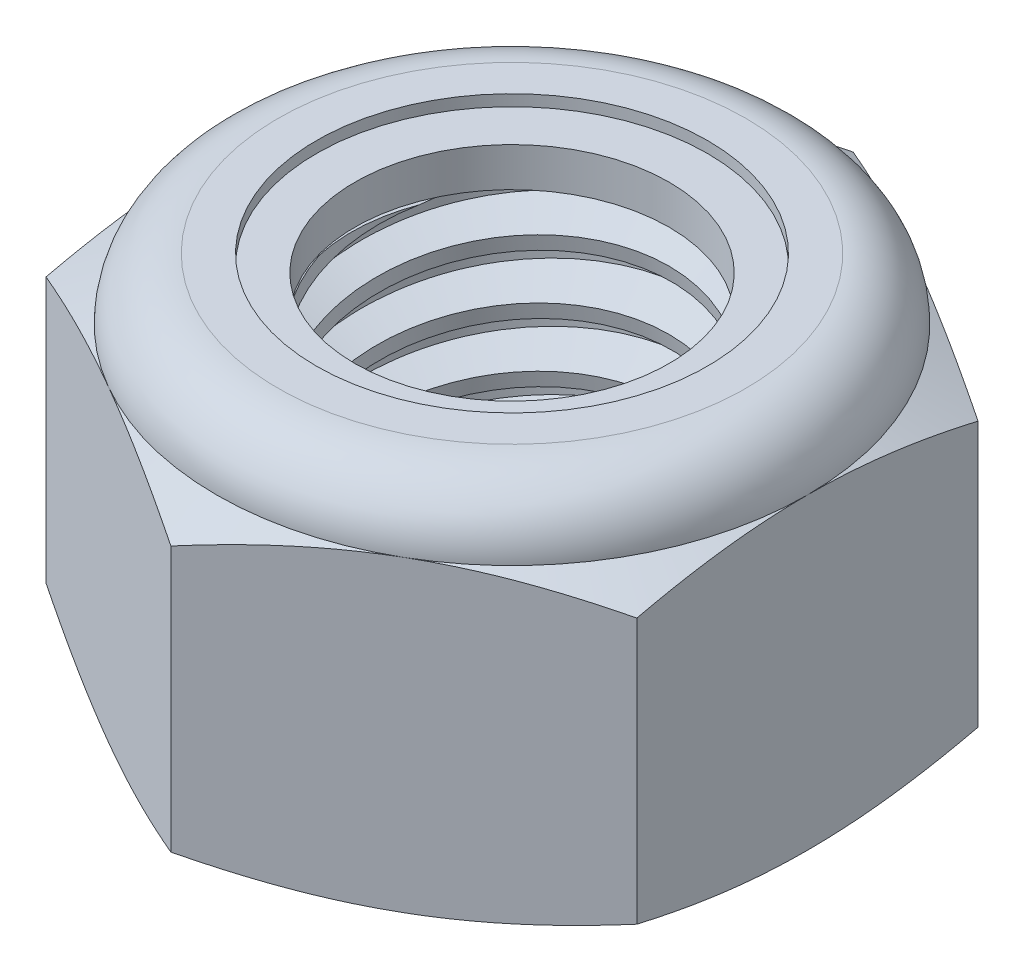
SolidWorks part; units mm, degrees
material "Stainless Steel (ferritic)"
ref_plane "Front" through (0, 0, 0) normal (0, 0, 1) x (1, 0, 0)
ref_plane "Top" through (0, 0, 0) normal (0, 1, 0) x (1, 0, 0)
ref_plane "Right" through (0, 0, 0) normal (1, 0, 0) x (0, 0, -1)
sketch "Sketch1" plane through (0, 0, 0) normal (0, 1, 0) x (1, 0, 0)
  line L1 (0, 4.6188) -> (-4, 2.3094)
  line L2 (-4, 2.3094) -> (-4, -2.3094)
  line L3 (-4, -2.3094) -> (0, -4.6188)
  line L4 (0, -4.6188) -> (4, -2.3094)
  line L5 (4, -2.3094) -> (4, 2.3094)
  line L6 (4, 2.3094) -> (0, 4.6188)
  circle A0 centre (0, 0) radius 4 construction
  dimension "Hex Flats" = 8
extrude "Extrude1" add sketch "Sketch1" along normal blind 5
sketch "Sketch2" plane through (0, 0, 0) normal (1, 0, 0) x (0, 0, -1)
  line L0 (-2.5, 0) -> (-2.5, 5) construction
  line L1 (0, 0) -> (2.5, 0)
  line L2 (0, 0) -> (0, 5)
  line L3 (0, 5) -> (2.5, 5)
  line L4 (2.5, 0) -> (2.5, 5)
  line L5 (-2.3094, 5) -> (2.3094, 5) construction
  line L7 (0, -2.5) -> (0, 0) construction
  dimension "Thread Dia" = 5
revolve "Revolve1" add sketch "Sketch2" angle 360 about L7
sketch "Sketch3" plane through (0, 0, 0) normal (1, 0, 0) x (0, 0, -1)
  line L0 (2.5, 5) -> (-2.5, 5) construction
  line L1 (-2.5, 5) -> (-2.5, 4.2) construction
  line L2 (-2.5, 4.2) -> (2.5, 5) construction
  line L3 (2.5, 5) -> (2.5158, 4.9013) construction
  line L4 (2.5158, 4.9013) -> (2.6264, 4.21)
  line L5 (2.6264, 4.21) -> (2.1593, 4.3885)
  line L6 (2.1593, 4.3885) -> (2.1277, 4.586)
  line L7 (2.1277, 4.586) -> (2.5158, 4.9013)
  line L8 (2.1435, 4.4872) -> (2.5711, 4.5557) construction
  line L9 (2.5, 5) -> (2.5, 4.5443) construction
  line L10 (2.5, 4.5443) -> (-2.5, 3.7443) construction
  line L11 (-2.5, 3.7443) -> (-2.5, 4.2) construction
  line L12 (-0.1369, 5) -> (0.1369, 3.2886) construction
  line L13 (-2.5, 0) -> (-2.5, 5) construction
  line L14 (0, 5) -> (2.5, 5) construction
  line L15 (2.5, 0) -> (2.5, 5) construction
  point P13 (0, 4.1443)
  dimension "D1" = 0.1
  dimension "D2" = 0.2
  dimension "Thread Pitch" = 0.8
  dimension "D4" = 60
  dimension "D5" = 0.8
revolve "Cut-Revolve1" cut sketch "Sketch3" angle 360 about L12
pattern_linear "LPattern1" count 6 spacing 0.8 along (0, -1, 0) count 2 spacing 0.8 along (0, 1, 0) of "Cut-Revolve1"
sketch "Sketch4" plane through (0, 0, 0) normal (1, 0, 0) x (0, 0, -1)
  line L0 (0, 5) -> (2.5, 5)
  line L1 (2.5, 5) -> (2.1277, 4.8264)
  line L2 (2.1277, 4.8264) -> (2.1277, 0.1736)
  line L3 (2.1277, 0.1736) -> (2.5, 0)
  line L4 (2.5, 0) -> (0, 0)
  line L5 (0, 0) -> (0, 5)
  line L6 (2.5, 0) -> (2.5, 5) construction
  line L7 (0, 5) -> (2.5, 5) construction
  line L8 (0, 0) -> (2.5, 0) construction
  line L9 (0, 0) -> (0, 5) construction
  line L10 (0, 5) -> (0, 5.4108) construction
  dimension "D1" = 25
revolve "Cut-Revolve2" cut sketch "Sketch4" angle 360 about L10
combine bodies "Combine1" operation type subtract main body 112 bodies to subtract 111
sketch "Sketch5" plane through (0, 0, 0) normal (1, 0, 0) x (0, 0, -1)
  line L0 (0, 0) -> (4, 0)
  line L1 (4, 0) -> (4.6188, 0.2886)
  line L2 (4.6188, 0.2886) -> (4.6188, 3.8781)
  line L3 (4.6188, 3.8781) -> (4, 4.1667)
  line L4 (3.1667, 5) -> (3.1667, 6.27)
  line L5 (3.1667, 6.27) -> (5.8888, 6.27)
  line L6 (5.8888, 6.27) -> (5.8888, -1.27)
  line L7 (5.8888, -1.27) -> (0, -1.27)
  line L8 (0, -1.27) -> (0, 0)
  line L9 (4, 4.1667) -> (4, 0) construction
  line L10 (0, 0) -> (2.5, 0) construction
  line L13 (4.6188, 2.0833) -> (5.8888, 2.0833) construction
  line L14 (4.6188, 5) -> (4.6188, 0) construction
  line L15 (0, 0) -> (0, 6.27) construction
  line L20 (0, 6.27) -> (3.1667, 6.27) construction
  line L22 (0, 5) -> (2.5, 5) construction
  arc A0 (4, 4.1667) -> (3.1667, 5) centre (3.1667, 4.1667) ccw
  dimension "D1" = 25
  dimension "D2" = 1.27
  dimension "D3" = 5
  dimension "D4" = 0.8333
revolve "Cut-Revolve3" cut sketch "Sketch5" angle 360 about L15
sketch "Sketch6" plane through (0, 0, 0) normal (1, 0, 0) x (0, 0, -1)
  line L0 (0, 4.1667) -> (3.8476, 4.1667)
  line L1 (3.1667, 4.8476) -> (2.6472, 4.8476)
  line L2 (0, 6.27) -> (0, 4.1667)
  line L3 (2.6472, 6.27) -> (0, 6.27)
  line L4 (0, 6.27) -> (3.1667, 6.27) construction
  line L5 (0, 0) -> (0, 6.27) construction
  line L6 (0, 6.27) -> (0, 44.323) construction
  line L7 (2.6472, 4.8476) -> (2.6472, 6.27)
  line L8 (3.1667, 5) -> (3.1667, 4.8476) construction
  line L9 (2.6472, 4.8476) -> (2.1277, 4.8476) construction
  line L10 (2.1277, 4.8476) -> (2.1277, 4.8264) construction
  arc A0 (3.8476, 4.1667) -> (3.1667, 4.8476) centre (3.1667, 4.1667) ccw
  arc A1 (4, 4.1667) -> (3.1667, 5) centre (3.1667, 4.1667) ccw construction
  dimension "D1" = 0.1524
revolve "Cut-Revolve4" cut sketch "Sketch6" angle 360 about L6
sketch "Sketch7" plane through (0, 0, 0) normal (1, 0, 0) x (0, 0, -1)
  line L0 (2.1277, 4.2429) -> (3.7666, 4.2429)
  line L1 (3.1667, 4.7714) -> (2.1277, 4.7714)
  line L2 (2.1277, 4.7714) -> (2.1277, 4.2429)
  line L3 (2.1277, 4.2429) -> (0, 4.2429) construction
  line L4 (0, 4.2429) -> (0, 4.7714) construction
  line L5 (0, 4.7714) -> (2.1277, 4.7714) construction
  line L6 (2.1277, 4.2429) -> (2.1277, 4.1667) construction
  line L7 (0, 4.1667) -> (3.8476, 4.1667) construction
  line L8 (3.1667, 4.7714) -> (3.1667, 4.8476) construction
  arc A0 (3.7666, 4.2429) -> (3.1667, 4.7714) centre (3.1667, 4.1667) ccw
  arc A2 (3.8476, 4.1667) -> (3.1667, 4.8476) centre (3.1667, 4.1667) ccw construction
  dimension "D1" = 0.0762
revolve "Revolve2" add sketch "Sketch7" angle 360 about L4
equation "\"D1@Sketch3\"=\"Thread Pitch@Sketch3\"/8"
equation "\"D2@Sketch3\"=\"Thread Pitch@Sketch3\"/4"
equation "\"D5@Sketch3\"=\"Thread Pitch@Sketch3\""
equation "\"D4@LPattern1\"=\"Thread Pitch@Sketch3\""
equation "\"D3@LPattern1\"=\"Thread Pitch@Sketch3\""
equation "\"D1@LPattern1\"=\"Height@Extrude1\"/\"Thread Pitch@Sketch3\""
equation "\"D4@Sketch5\"=\"Height@Extrude1\"/6"
